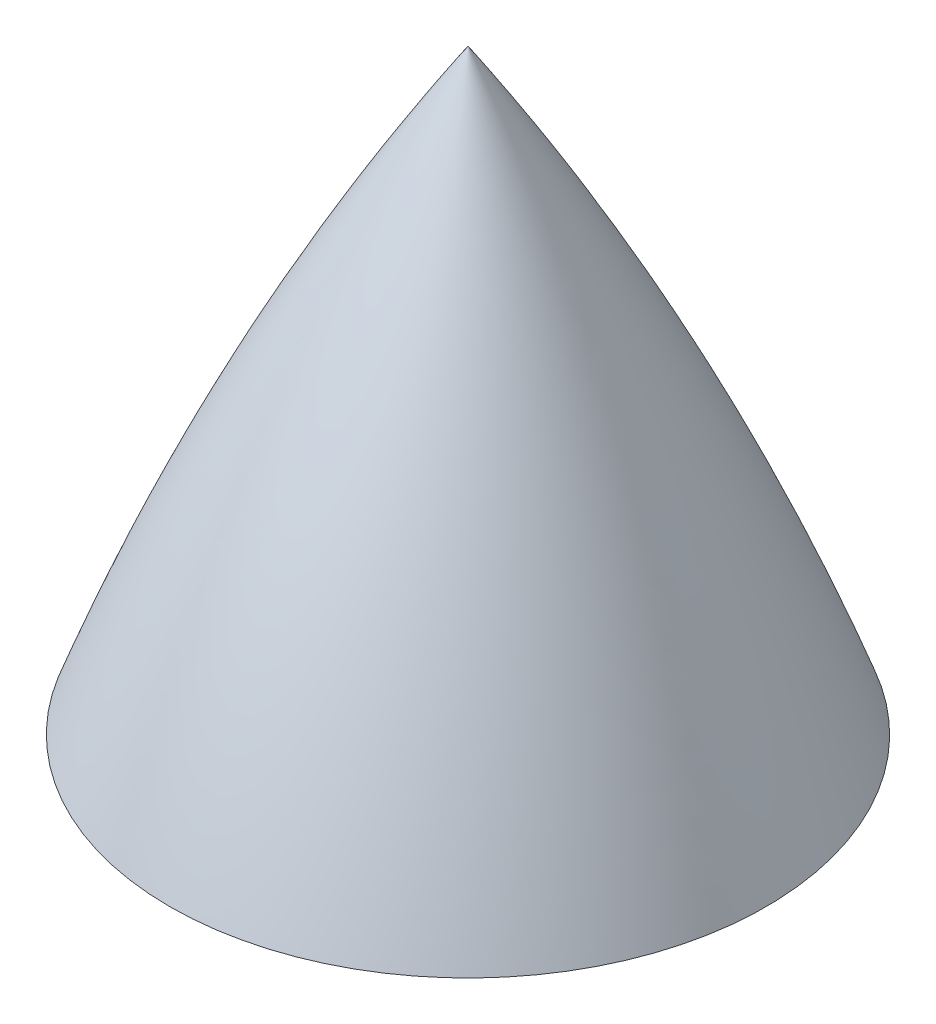
SolidWorks part; units mm, degrees
material "纯铅"
ref_plane "前视基准面" through (0, 0, 0) normal (0, 0, 1) x (1, 0, 0)
ref_plane "上视基准面" through (0, 0, 0) normal (0, 1, 0) x (1, 0, 0)
ref_plane "右视基准面" through (0, 0, 0) normal (1, 0, 0) x (0, 0, -1)
sketch "草图1" plane through (0, 0, 0) normal (1, 0, 0) x (0, 0, -1)
  line L0 (0, 0) -> (0, 0.4)
  line L1 (-0.2, 0.4) -> (-0.2, 0)
  line L2 (-0.2, 0) -> (0, 0)
  spline S0 degree 2 poles (0, 0.0189) (0.0005, 0.0099) (0, 0) knots 0.877274 0.877274 0.877274 1 1 1
  spline S1 degree 2 poles (-0.2, 0.4) (-0.0759, 0.2104) (0, 0) knots 0 0 0 1 1 1
  dimension "D1" = 0.4
revolve "旋转1" add sketch "草图1" angle 360 about L1
